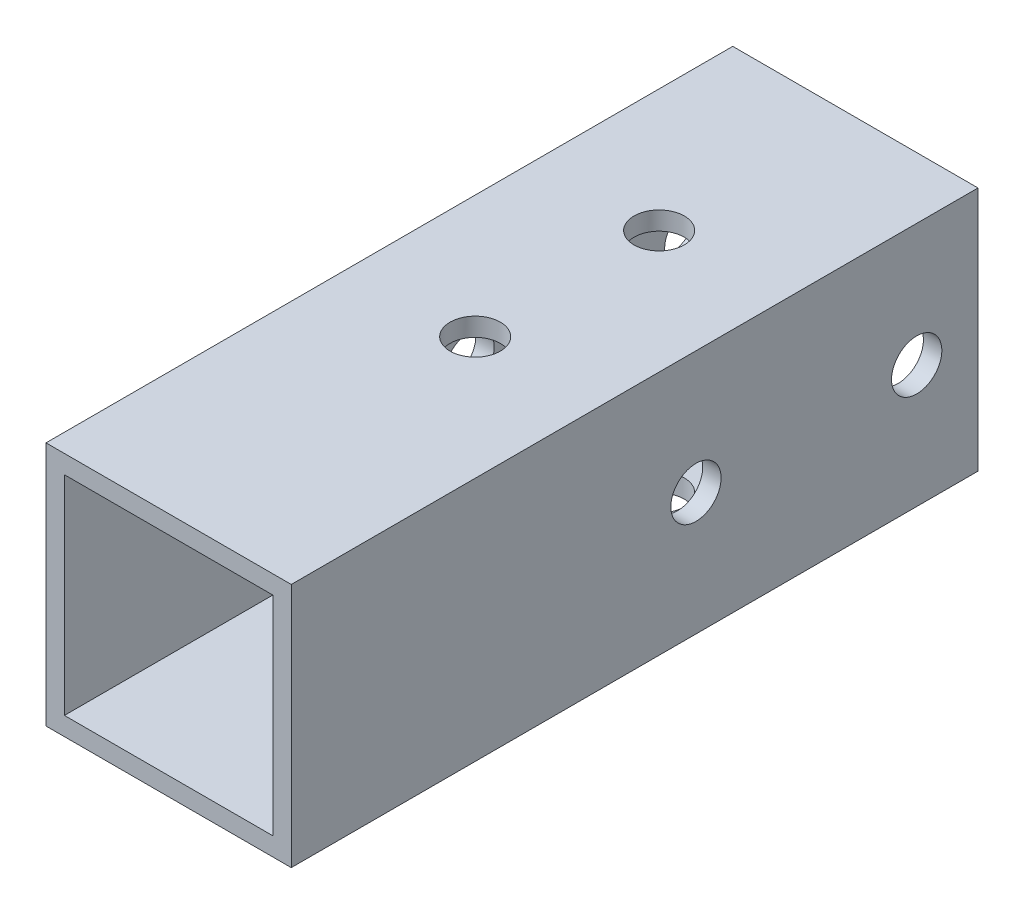
SolidWorks part; units mm, degrees
ref_plane "前视基准面" through (0, 0, 0) normal (0, 0, 1) x (1, 0, 0)
ref_plane "上视基准面" through (0, 0, 0) normal (0, 1, 0) x (1, 0, 0)
ref_plane "右视基准面" through (0, 0, 0) normal (1, 0, 0) x (0, 0, -1)
sketch "草图1" plane through (0, 0, 0) normal (0, 0, 1) x (1, 0, 0)
  line L1 (-10, 10) -> (10, 10)
  line L2 (-10, 10) -> (-10, -10)
  line L3 (-10, -10) -> (10, -10)
  line L4 (10, 10) -> (10, -10)
  line L5 (-10, 10) -> (10, -10) construction
  line L6 (-10, -10) -> (10, 10) construction
  line L7 (-8.5, 8.5) -> (8.5, 8.5)
  line L8 (-8.5, 8.5) -> (-8.5, -8.5)
  line L9 (-8.5, -8.5) -> (8.5, -8.5)
  line L10 (8.5, 8.5) -> (8.5, -8.5)
  line L11 (-8.5, 8.5) -> (8.5, -8.5) construction
  line L12 (-8.5, -8.5) -> (8.5, 8.5) construction
  point P0 (0, 0)
  point P5 (0, 0)
  dimension "D1" = 20
  dimension "D2" = 20
  dimension "D3" = 1.5
  dimension "D4" = 1.5
extrude "凸台-拉伸1" add sketch "草图1" along normal blind 56
sketch "草图3" plane through (-10, 0, 0) normal (-1, 0, 0) x (0, 0, 1)
  circle A0 centre (5, 0) radius 2.05
  circle A1 centre (23, 0) radius 2.05
  dimension "D1" = 4.1
  dimension "D2" = 5
  dimension "D3" = 18
extrude "切除-拉伸1" cut sketch "草图3" against normal blind 23
sketch "草图4" plane through (0, 10, 0) normal (0, 1, 0) x (1, 0, 0)
  line L0 (10, -56) -> (-10, -56) construction
  circle A0 centre (0, -16) radius 2.05
  circle A1 centre (0, -31) radius 2.05
  dimension "D1" = 4.1
  dimension "D2" = 25
  dimension "D3" = 15
extrude "切除-拉伸2" cut sketch "草图4" against normal blind 23
